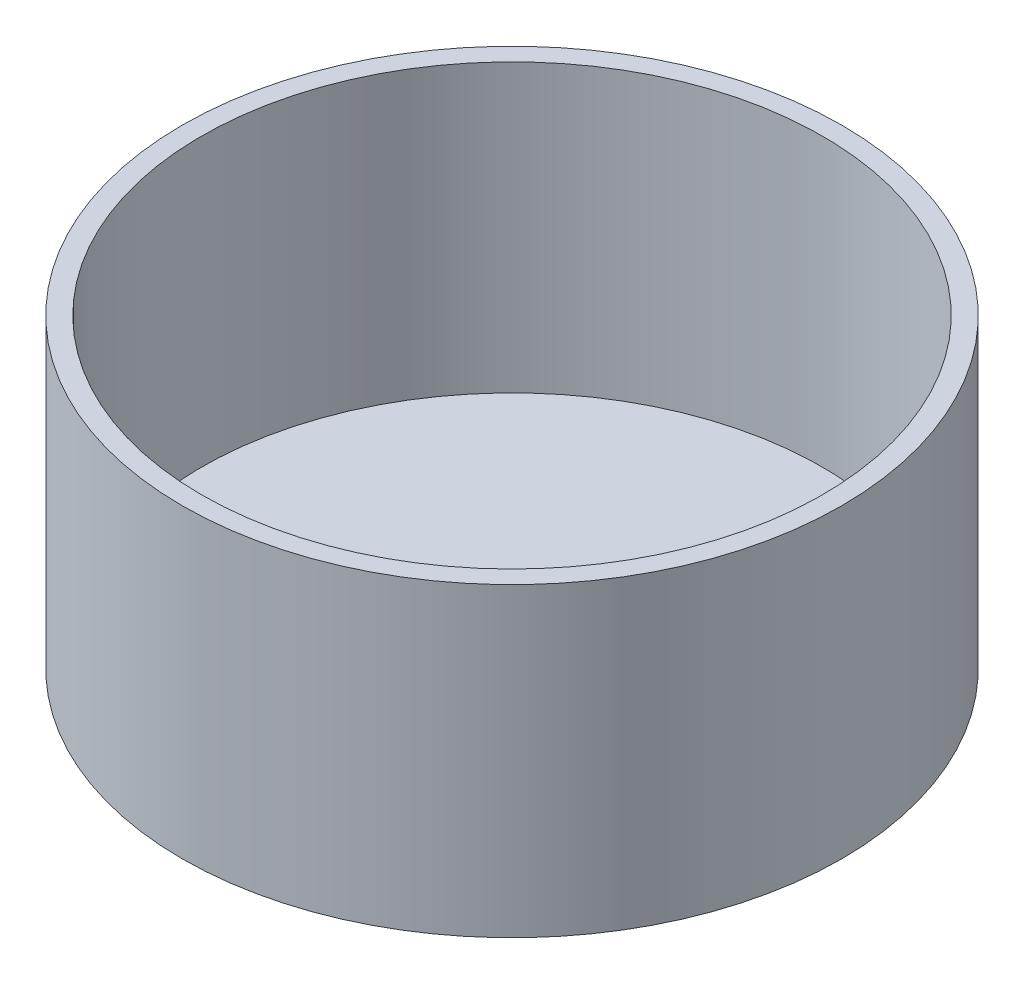
SolidWorks part; units mm, degrees
ref_plane "Alzado" through (0, 0, 0) normal (0, 0, 1) x (1, 0, 0)
ref_plane "Planta" through (0, 0, 0) normal (0, 1, 0) x (1, 0, 0)
ref_plane "Vista lateral" through (0, 0, 0) normal (1, 0, 0) x (0, 0, -1)
sketch "Croquis1" plane through (0, 0, 0) normal (0, 1, 0) x (1, 0, 0)
  circle A0 centre (0, 0) radius 32.5
  dimension "D1" = 65
extrude "Saliente-Extruir1" add sketch "Croquis1" along normal blind 30
shell "Vaciado1" thickness 2
